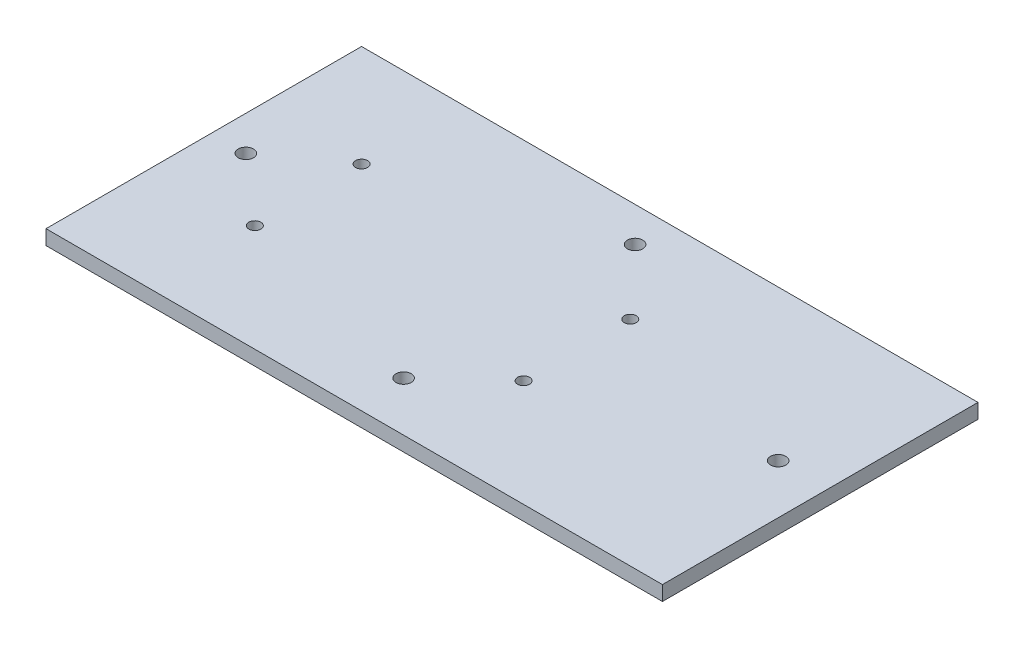
SolidWorks part; units mm, degrees
ref_plane "Front Plane" through (0, 0, 0) normal (0, 0, 1) x (1, 0, 0)
ref_plane "Top Plane" through (0, 0, 0) normal (0, 1, 0) x (1, 0, 0)
ref_plane "Right Plane" through (0, 0, 0) normal (1, 0, 0) x (0, 0, -1)
sketch "Sketch1" plane through (0, 0, 0) normal (0, 1, 0) x (1, 0, 0)
  line L0 (0, 34.0875) -> (0, -34.0875) construction
  line L1 (-66.5875, 34.0875) -> (66.5875, 34.0875)
  line L2 (-66.5875, 34.0875) -> (-66.5875, -34.0875)
  line L3 (-66.5875, -34.0875) -> (66.5875, -34.0875)
  line L4 (66.5875, 34.0875) -> (66.5875, -34.0875)
  line L5 (-66.5875, 34.0875) -> (66.5875, -34.0875) construction
  line L6 (-66.5875, -34.0875) -> (66.5875, 34.0875) construction
  line L7 (-59.0875, 26.5875) -> (55.9125, 26.5875) construction
  line L8 (-59.0875, 26.5875) -> (-59.0875, -23.4125) construction
  line L9 (-59.0875, -23.4125) -> (55.9125, -23.4125) construction
  line L10 (55.9125, 26.5875) -> (55.9125, -23.4125) construction
  line L11 (-66.5875, 0) -> (66.5875, 0) construction
  circle A0 centre (0, 26.5875) radius 1.65
  circle A1 centre (-59.0875, 1.5875) radius 1.65
  circle A2 centre (55.9125, 1.5875) radius 1.65
  circle A3 centre (0, -23.4125) radius 1.65
  point P0 (0, 0)
  point P6 (0, 0)
  dimension "D7" = 3.3
  dimension "D1" = 133.175
  dimension "D2" = 7.5
  dimension "D3" = 7.5
  dimension "D4" = 10.675
  dimension "D5" = 10.675
  dimension "D6" = 68.175
extrude "Boss-Extrude1" add sketch "Sketch1" along normal blind 3.175
sketch "Sketch2" plane through (0, 0, 0) normal (0, -1, 0) x (1, 0, 0)
  line L0 (66.5875, -34.0875) -> (-66.5875, -34.0875) construction
  line L1 (-44.5875, 10.9625) -> (13.4625, 10.9625) construction
  line L2 (-44.5875, 10.9625) -> (-44.5875, -12.0875) construction
  line L3 (-44.5875, -12.0875) -> (13.4625, -12.0875) construction
  line L4 (13.4625, 10.9625) -> (13.4625, -12.0875) construction
  line L5 (-44.5875, 10.9625) -> (13.4625, -12.0875) construction
  line L6 (-44.5875, -12.0875) -> (13.4625, 10.9625) construction
  line L7 (-66.5875, -34.0875) -> (-66.5875, 34.0875) construction
  circle A0 centre (-44.5875, 10.9625) radius 1.3
  circle A1 centre (-44.5875, -12.0875) radius 1.3
  circle A2 centre (13.4625, -12.0875) radius 1.3
  circle A3 centre (13.4625, 10.9625) radius 1.3
  point P0 (-15.5625, -0.5625)
  dimension "D3" = 2.6
  dimension "D1" = 58.05
  dimension "D2" = 23.05
  dimension "D4" = 22
  dimension "D5" = 22
extrude "Cut-Extrude1" cut sketch "Sketch2" against normal up to surface (3.175 mm away) up to face at (55.9125, 3.175, 0.0625)
